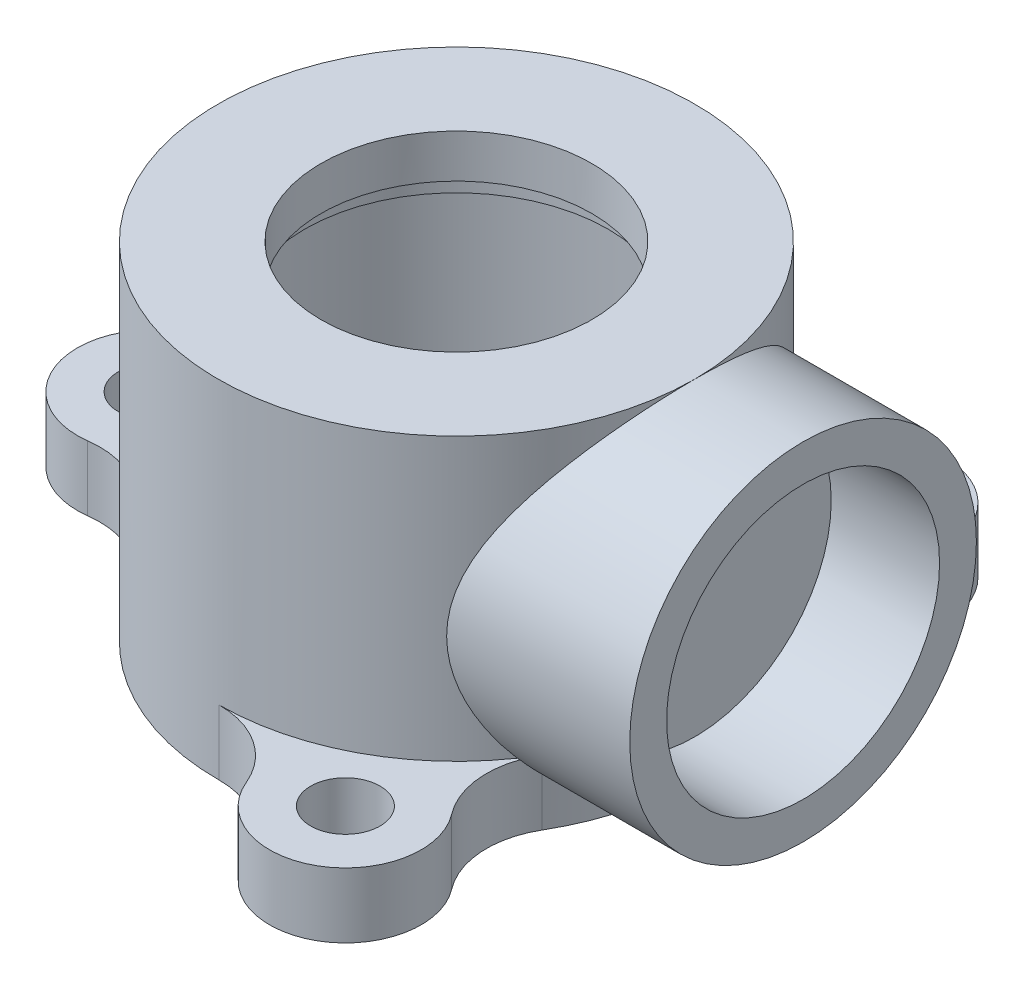
SolidWorks part; units mm, degrees
ref_plane "前视基准面" through (0, 0, 0) normal (0, 0, 1) x (1, 0, 0)
ref_plane "上视基准面" through (0, 0, 0) normal (0, 1, 0) x (1, 0, 0)
ref_plane "右视基准面" through (0, 0, 0) normal (1, 0, 0) x (0, 0, -1)
sketch "草图1" plane through (0, 0, 0) normal (0, 1, 0) x (1, 0, 0)
  circle A0 centre (0, 0) radius 11
  dimension "D1" = 22
extrude "凸台-拉伸1" add sketch "草图1" along normal blind 16
sketch "草图2" plane through (0, 16, 0) normal (0, 1, 0) x (1, 0, 0)
  circle A0 centre (0, 0) radius 6.25
  dimension "D1" = 12.5
extrude "切除-拉伸1" cut sketch "草图2" against normal up to next
sketch "草图3" plane through (0, 0, 0) normal (0, -1, 0) x (1, 0, 0)
  circle A0 centre (0, 0) radius 9.25
  dimension "D1" = 18.5
extrude "切除-拉伸2" cut sketch "草图3" against normal offset from surface (13 mm away) 3 up to face at (0, 16, 6.25)
ref_plane "基准面1" through (16, 0, 0) normal (1, 0, 0) x (0, 0, -1)
sketch "草图4" plane through (16, 0, 0) normal (1, 0, 0) x (0, 0, -1)
  line L0 (0, 18.2452) -> (0, -1.2924) construction
  circle A1 centre (0, 8) radius 8
  dimension "D1" = 8
  dimension "D3" = 16
extrude "凸台-拉伸2" add sketch "草图4" against normal up to surface (8.4502 mm away)
sketch "草图5" plane through (16, 0, 0) normal (1, 0, 0) x (0, 0, -1)
  circle A0 centre (0, 8) radius 6.3
  dimension "D1" = 12.6
extrude "切除-拉伸3" cut sketch "草图5" against normal blind 5
sketch "草图6" plane through (0, 0, 0) normal (0, -1, 0) x (1, 0, 0)
  line L0 (-14.7982, 0) -> (22.3903, 0) construction
  circle A2 centre (-14, 0) radius 1.6
  circle A3 centre (-14, 0) radius 3.5
  circle A4 centre (0, 0) radius 11 construction
  arc A5 (-9.553, 5.4535) -> (-9.553, -5.4535) centre (0, 0) ccw
  arc A6 (-13.5458, 3.4704) -> (-9.553, 5.4535) centre (-13.0268, 7.4366) ccw
  arc A7 (-13.5458, -3.4704) -> (-9.553, -5.4535) centre (-13.0268, -7.4366) cw
  circle A8 centre (7, 12.1244) radius 3.5
  circle A9 centre (7, 12.1244) radius 1.6
  arc A10 (3.7675, 13.4662) -> (0.0536, 10.9999) centre (0.0731, 14.9998) cw
  arc A11 (9.4994, 5.5464) -> (0.0536, 10.9999) centre (0, 0) ccw
  arc A12 (9.7784, 9.9958) -> (9.4994, 5.5464) centre (12.9537, 7.5632) ccw
  circle A13 centre (7, -12.1244) radius 3.5
  circle A14 centre (7, -12.1244) radius 1.6
  arc A15 (9.7784, -9.9958) -> (9.4994, -5.5464) centre (12.9537, -7.5632) cw
  arc A16 (0.0536, -10.9999) -> (9.4994, -5.5464) centre (0, 0) ccw
  arc A17 (3.7675, -13.4662) -> (0.0536, -10.9999) centre (0.0731, -14.9998) ccw
  point P35 (0, 0)
  dimension "D1" = 3.2
  dimension "D4" = 8
  dimension "D2" = 7
  dimension "D3" = 14
  dimension "D5" = 3
extrude "凸台-拉伸3" add sketch "草图6" against normal blind 3
sketch "草图7" plane through (0, 13, 0) normal (0, -1, 0) x (1, 0, 0)
  circle A0 centre (0, 0) radius 7
  dimension "D1" = 14
extrude "切除-拉伸4" cut sketch "草图7" against normal blind 1
